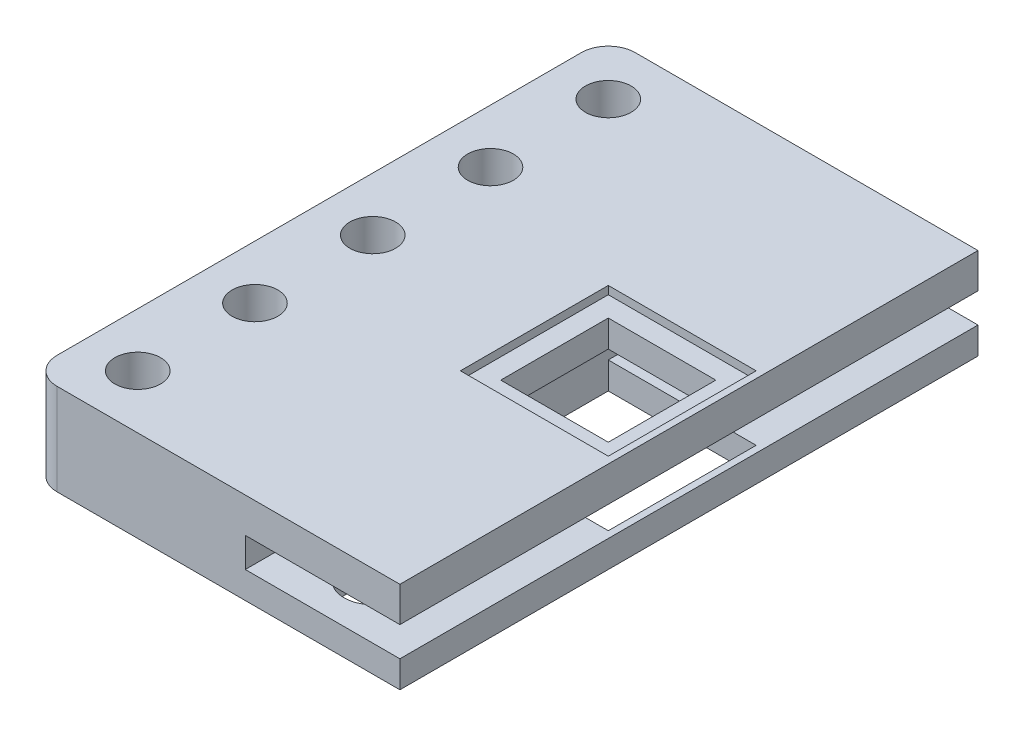
SolidWorks part; units mm, degrees
ref_plane "Front Plane" through (0, 0, 0) normal (0, 0, 1) x (1, 0, 0)
ref_plane "Top Plane" through (0, 0, 0) normal (0, 1, 0) x (1, 0, 0)
ref_plane "Right Plane" through (0, 0, 0) normal (1, 0, 0) x (0, 0, -1)
sketch "Sketch1" plane through (0, 0, 0) normal (0, 1, 0) x (1, 0, 0)
  line L1 (-14.684, 10.0891) -> (6.816, 10.0891)
  line L2 (-14.684, 10.0891) -> (-14.684, -11.4109)
  line L3 (-14.684, -11.4109) -> (6.816, -11.4109)
  line L4 (6.816, 10.0891) -> (6.816, -11.4109)
  dimension "D1" = 21.5
  dimension "D2" = 21.5
extrude "Boss-Extrude1" add sketch "Sketch1" along normal blind 3.1
sketch "Sketch2" plane through (0, 0, 11.4109) normal (0, 0, 1) x (1, 0, 0)
  line L7 (-14.684, 3.1) -> (6.816, 3.1) construction
  line L8 (-6.684, 2.1) -> (-1.184, 2.1)
  line L9 (-6.684, 2.1) -> (-6.684, 1)
  line L10 (-6.684, 1) -> (-1.184, 1)
  line L11 (-1.184, 2.1) -> (-1.184, 1)
  line L12 (6.816, 3.1) -> (6.816, 0) construction
  dimension "D1" = 5.5
  dimension "D4" = 8
  dimension "D2" = 1.1
  dimension "D3" = 1
extrude "Cut-Extrude1" cut sketch "Sketch2" against normal through all
sketch "Sketch3" plane through (0, 3.1, 0) normal (0, 1, 0) x (1, 0, 0)
  line L10 (6.816, 10.0891) -> (-14.684, 10.0891) construction
  line L15 (-6.684, 2.0891) -> (-1.184, 2.0891)
  line L16 (-6.684, 2.0891) -> (-6.684, -3.4109)
  line L17 (-6.684, -3.4109) -> (-1.184, -3.4109)
  line L18 (-1.184, 2.0891) -> (-1.184, -3.4109)
  line L21 (-14.684, 10.0891) -> (-14.684, -11.4109) construction
  dimension "D1" = 5.5
  dimension "D2" = 5.5
  dimension "D3" = 8
  dimension "D4" = 8
extrude "Boss-Extrude2" add sketch "Sketch3" along normal blind 0.3
sketch "Sketch11" plane through (0, 3.1, 0) normal (0, 1, 0) x (1, 0, 0)
  line L0 (6.816, -11.4109) -> (6.816, 10.0891) construction
  line L1 (-5.934, -2.6609) -> (-1.934, -2.6609)
  line L2 (-5.934, -2.6609) -> (-5.934, 1.3391)
  line L3 (-5.934, 1.3391) -> (-1.934, 1.3391)
  line L4 (-1.934, -2.6609) -> (-1.934, 1.3391)
  line L5 (-5.934, -2.6609) -> (-1.934, 1.3391) construction
  line L6 (-5.934, 1.3391) -> (-1.934, -2.6609) construction
  line L7 (6.816, 10.0891) -> (-14.684, 10.0891) construction
  point P0 (-3.934, -0.6609)
  point P5 (0, 0)
  dimension "D1" = 4
  dimension "D2" = 4
  dimension "D3" = 10.75
  dimension "D4" = 10.75
extrude "Cut-Extrude2" cut sketch "Sketch11" against normal through all
sketch "Sketch12" plane through (0, 3.4, 0) normal (0, 1, 0) x (1, 0, 0)
  line L0 (-14.684, 10.0891) -> (-14.684, -11.4109) construction
  line L1 (6.816, 10.0891) -> (-14.684, 10.0891) construction
  line L2 (6.816, -11.4109) -> (6.816, 10.0891) construction
  line L3 (-14.684, -11.4109) -> (6.816, -11.4109) construction
  circle A0 centre (-12.684, 8.0891) radius 0.6038
  circle A2 centre (-12.684, -9.4109) radius 0.6038
  circle A3 centre (4.816, 8.0891) radius 0.6038
  circle A4 centre (4.816, -9.4109) radius 0.6038
  circle A5 centre (-12.684, 3.7091) radius 0.6038
  circle A6 centre (-12.684, -5.0509) radius 0.6038
  circle A7 centre (-12.684, -0.6709) radius 0.6038
  point P8 (-12.684, 3.918)
  point P11 (-12.684, 0)
  point P14 (-4.1561, 8.0891)
  point P17 (-4.1561, 0)
  point P22 (-12.684, 2.9347)
  point P25 (-12.684, -5.7911)
  point P28 (-12.684, -1.5986)
  point P29 (-12.684, 4.7275)
  dimension "D1" = 2
  dimension "D2" = 2
  dimension "D3" = 2
  dimension "D4" = 2
  dimension "D5" = 2
  dimension "D6" = 2
  dimension "D7" = 2
  dimension "D8" = 2
  dimension "D9" = 4.38
  dimension "D10" = 4.38
  dimension "D11" = 4.38
hole_wizard "Tap Drill for M2x0.4 Tap3" positions "Sketch13" profile "Sketch14" hole size "M2x0.4" standard "ANSI Metric" end condition through all
sketch "Sketch13" plane through (0, 3.4, 0) normal (0, 1, 0) x (1, 0, 0)
  point P0 (-12.684, 8.0891)
  point P3 (4.816, 8.0891)
  point P6 (4.816, -9.4109)
  point P9 (-12.684, -9.4109)
  point P13 (-12.684, 3.7091)
  point P16 (-12.684, -0.6709)
  point P19 (-12.684, -5.0509)
sketch "Sketch14" plane through (-12.684, 3.4, -8.0891) normal (1, 0, 0) x (0, 0, 1)
  line L0 (0, 0) -> (0, 3.4)
  line L1 (0, 3.4) -> (0.85, 3.4)
  line L2 (0.85, 3.4) -> (0.85, 0)
  line L5 (0.85, 0) -> (0, 0)
  line L11 (0, -6.35) -> (0, 107.95) construction
  dimension "Thru Hole Dia." = 1.7
  dimension "Thru Hole Depth" = 3.4
sketch "Sketch15" plane through (0, 0, 0) normal (0, -1, 0) x (1, 0, 0)
  line L0 (6.816, 11.4109) -> (6.816, -10.0891) construction
  line L1 (6.816, -10.0891) -> (-14.684, -10.0891) construction
  line L2 (-14.684, 11.4109) -> (6.816, 11.4109) construction
  line L3 (-1.934, -1.3391) -> (-5.934, -1.3391) construction
  line L4 (-5.934, 2.6609) -> (-1.934, 2.6609) construction
  circle A0 centre (-3.934, -8.0891) radius 0.657
  circle A1 centre (-3.934, 9.4109) radius 0.657
  circle A2 centre (-3.934, -4.5391) radius 0.657
  circle A3 centre (-3.934, 5.8609) radius 0.657
  point P8 (-8.684, 0)
  point P13 (-3.934, -4.4676)
  point P16 (-3.934, 4.9803)
  dimension "D1" = 10.75
  dimension "D2" = 2
  dimension "D3" = 2
  dimension "D4" = 0
  dimension "D5" = 3.2
  dimension "D6" = 3.2
hole_wizard "Tap Drill for M2.5x0.45 Tap1" positions "Sketch16" profile "Sketch17" hole size "M2.5x0.45" standard "ANSI Metric"
sketch "Sketch16" plane through (0, 0, 0) normal (0, -1, 0) x (-1, 0, 0)
  point P0 (3.934, 8.0891)
  point P3 (3.934, -9.4109)
  point P7 (3.934, 4.5391)
  point P10 (3.934, -5.8609)
sketch "Sketch17" plane through (-3.934, 0, -8.0891) normal (1, 0, 0) x (0, 0, -1)
  line L0 (0, 0) -> (0, 1)
  line L1 (0, 1) -> (1.075, 1)
  line L2 (1.075, 1) -> (1.075, 0)
  line L5 (1.075, 0) -> (0, 0)
  line L11 (0, -6.35) -> (0, 107.95) construction
  dimension "Thru Hole Dia." = 2.15
  dimension "Thru Hole Depth" = 1
sketch "Sketch18" plane through (0, 0, 0) normal (0, -1, 0) x (1, 0, 0)
  line L0 (6.816, 11.4109) -> (6.816, -10.0891) construction
  line L1 (-1.184, 3.4109) -> (-6.684, 3.4109)
  line L2 (-1.184, 3.4109) -> (-1.184, -2.0891)
  line L3 (-1.184, -2.0891) -> (-6.684, -2.0891)
  line L4 (-6.684, 3.4109) -> (-6.684, -2.0891)
  line L5 (-1.184, 3.4109) -> (-6.684, -2.0891) construction
  line L6 (-1.184, -2.0891) -> (-6.684, 3.4109) construction
  line L7 (6.816, -10.0891) -> (-14.684, -10.0891) construction
  point P0 (-3.934, 0.6609)
  dimension "D1" = 5.5
  dimension "D2" = 5.5
  dimension "D3" = 10.75
  dimension "D4" = 10.75
extrude "Cut-Extrude3" cut sketch "Sketch18" against normal up to next
fillet "Fillet3" radius 1 4 edges at (-14.684, 1.7, 11.4109) (6.816, 1.7, 11.4109) (6.816, 1.7, -10.0891) (-14.684, 1.7, -10.0891)
sketch "Sketch19" plane through (0, 3.4, 0) normal (0, 1, 0) x (1, 0, 0)
  line L0 (6.816, -10.4109) -> (6.816, 9.0891) construction
  line L1 (-1.184, 2.0891) -> (6.816, 2.0891)
  line L2 (-1.184, 2.0891) -> (-1.184, -3.4109)
  line L3 (-1.184, -3.4109) -> (6.816, -3.4109)
  line L4 (6.816, 2.0891) -> (6.816, -3.4109)
  line L5 (-6.684, -3.4109) -> (-1.184, -3.4109) construction
  line L6 (-1.184, 2.0891) -> (6.816, 7.4225)
  line L7 (-1.184, -3.4109) -> (6.816, -8.7442)
  dimension "D1" = 0
  dimension "D2" = 5.3333
  dimension "D3" = 5.3333
sketch "Sketch21" plane through (0, 3.4, 0) normal (0, 1, 0) x (1, 0, 0)
  line L1 (12.1906, 15.7376) -> (-0.934, 15.7376)
  line L2 (12.1906, 15.7376) -> (12.1906, -19.5605)
  line L3 (12.1906, -19.5605) -> (-0.934, -19.5605)
  line L4 (-0.934, 15.7376) -> (-0.934, -19.5605)
  line L5 (-1.184, 2.0891) -> (-1.184, -3.4109) construction
  dimension "D1" = 0.25
extrude "Cut-Extrude8" cut sketch "Sketch21" against normal through all
sketch "Sketch22" plane through (0, 0, -10.0891) normal (0, 0, -1) x (-1, 0, 0)
  line L0 (0.934, 3.4) -> (0.934, 0) construction
  line L1 (1.184, 1) -> (0.934, 1)
  line L2 (1.184, 1) -> (1.184, 2.1)
  line L3 (1.184, 2.1) -> (0.934, 2.1)
  line L4 (0.934, 1) -> (0.934, 2.1)
  line L5 (1.184, 2.1) -> (6.684, 2.1) construction
  dimension "D1" = 0
extrude "Cut-Extrude9" cut sketch "Sketch22" against normal through all
equation "\"samplewidth\" = 5 + \"dimtolerance\""
equation "\"D1@Sketch1\"=\"samplewidth\" + 2*\"border\""
equation "\"sampleheight\" = 5 + \"dimtolerance\""
equation "\"D2@Sketch1\"=\"sampleheight\" + 2*\"border\""
equation "\"stickthickness\" = 1.1"
equation "\"D1@Boss-Extrude1\"=\"stickthickness\"+2"
equation "\"stickwidth\" = 5.5"
equation "\"samplethickness\"= 0.3"
equation "\"D1@Boss-Extrude2\"=\"samplethickness\""
equation "\"dimtolerance\"= 0.5"
equation "\"border\" = 8"
equation "\"D3@Sketch3\"=\"border\""
equation "\"D4@Sketch2\"=(\"border\" + \"samplewidth\"/2) - (\"stickwidth\"/2)"
equation "\"windowwidth\" = 4"
equation "\"windowheight\" = 4"
equation "\"D3@Sketch11\"=\"border\" + \"samplewidth\"/2"
equation "\"D4@Sketch11\"=\"border\" + \"sampleheight\"/2"
equation "\"D1@Sketch15\"=\"border\" + \"samplewidth\"/2"
equation "\"D2@Sketch15\"=\"border\"*1/4"
equation "\"D3@Sketch18\"=\"border\" + \"samplewidth\"/2"
equation "\"D4@Sketch18\"=\"border\" + \"sampleheight\"/2"
equation "\"D2@Sketch11\"=\"windowheight\""
equation "\"D1@Sketch11\"=\"windowwidth\""
equation "\"D1@Sketch18\"=\"samplewidth\""
equation "\"D2@Sketch18\"= \"sampleheight\""
equation "\"D4@Sketch3\"= \"border\""
equation "\"D3@Sketch15\"=\"border\"*1/4"
equation "\"D5@Sketch15\"=\"border\"*2/5"
equation "\"D6@Sketch15\"=\"border\"*2/5"
equation "\"D2@Sketch19\"=\"border\"*2/3"
equation "\"D3@Sketch19\"=\"border\"*2/3"
equation "\"D2@Sketch2\"=\"stickthickness\""
